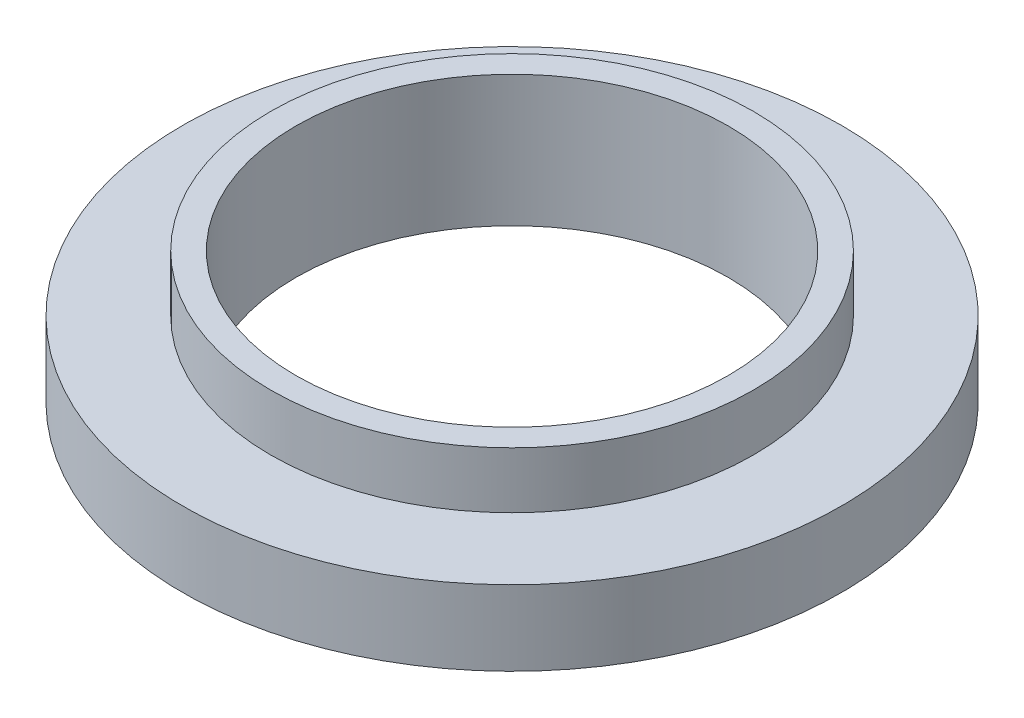
SolidWorks part; units mm, degrees
ref_plane "Front Plane" through (0, 0, 0) normal (0, 0, 1) x (1, 0, 0)
ref_plane "Top Plane" through (0, 0, 0) normal (0, 1, 0) x (1, 0, 0)
ref_plane "Right Plane" through (0, 0, 0) normal (1, 0, 0) x (0, 0, -1)
sketch "Sketch1" plane through (0, 0, 0) normal (0, 0, 1) x (1, 0, 0)
  line L0 (-31.75, 11.0119) -> (-31.75, 30.2842)
  line L1 (-54.35, 0) -> (-35.45, 0) construction
  line L2 (-31.75, 11.0119) -> (-31.75, 30.2842) construction
  line L3 (-31.75, 30.2842) -> (-35.45, 30.2842) construction
  line L4 (-35.45, 0) -> (-35.45, 30.2842) construction
  line L5 (-31.75, 30.2842) -> (-35.45, 30.2842)
  line L6 (-35.45, 30.2842) -> (-35.45, 22.0238)
  line L7 (-35.45, 22.0238) -> (-48.4, 22.0238)
  line L8 (-48.4, 22.0238) -> (-48.4, 11.0119)
  line L9 (-48.4, 11.0119) -> (-35.45, 11.0119) construction
  line L10 (-35.45, 11.0119) -> (-35.45, 0) construction
  line L11 (-35.45, 0) -> (-54.35, 0) construction
  line L12 (-37.9123, 11.0119) -> (-48.4, 11.0119)
  line L13 (0, 0) -> (0, 12.7515) construction
  line L14 (-37.9123, 11.0119) -> (-31.75, 11.0119)
  arc A0 (-35.45, 0) -> (-37.9123, 11.0119) centre (-37.9123, 5.2307) ccw construction
  dimension "D7" = 5.7813
  dimension "D1" = 31.75
  dimension "D2" = 3.7
  dimension "D3" = 30.2842
  dimension "D4" = 8.2604
  dimension "D5" = 48.4
  dimension "D6" = 11.0119
  dimension "D8" = 54.35
revolve "Revolve1" add sketch "Sketch1" angle 360 about L13
sketch "Sketch2" plane through (0, 22.0238, 0) normal (0, 1, 0) x (1, 0, 0)
  line L1 (4.1302, 55.0595) -> (-4.1302, 55.0595)
  line L2 (4.1302, 55.0595) -> (4.1302, 41.7405)
  line L3 (4.1302, 41.7405) -> (-4.1302, 41.7405)
  line L4 (-4.1302, 55.0595) -> (-4.1302, 41.7405)
  line L5 (4.1302, 55.0595) -> (-4.1302, 41.7405) construction
  line L6 (4.1302, 41.7405) -> (-4.1302, 55.0595) construction
  circle A0 centre (0, 0) radius 48.4 construction
  point P0 (0, 48.4)
  dimension "D1" = 8.2604
  dimension "D2" = 55.0595
sketch "Sketch7" plane through (0, 22.0238, 0) normal (0, 1, 0) x (1, 0, 0)
  point P3 (0, 0)
equation "\"D5@Sketch1\"=((\"Spring_inner_dia\"+\"Spring_wire_dia\")/2)*1.1"
equation "\"D6@Sketch1\"=\"Upper_Mount_largest_radius\"/1.68"
equation "\"D4@Sketch1\"=\"Upper_Mount_largest_radius\"/2.23960185"
equation "\"D2@Sketch1\"=\"Upper_Mount_largest_radius\"/5"
equation "\"D7@Sketch1\"=\"Upper_Mount_largest_radius\"/3.2"
equation "\"D1@Sketch1\"=\"Upper_Mount_largest_radius\"+\"Upper_mount_wall_thickness\"+1.25mm"
equation "\"D3@Sketch1\"=\"Upper_Mount_largest_radius\"/0.61087947"
equation "\"D2@Sketch2\"=\"Upper_Mount_largest_radius\"/0.336"
equation "\"D1@Sketch2\"=\"Upper_Mount_largest_radius\"/2.23960185"
equation "\"Upper_Mount_largest_radius\" =18.5"
equation "\"Upper_mount_wall_thickness\" =12"
equation "\"Lower_Mount_piston_rod_length\" =149"
equation "\"Lower_Mount_piston_rod_radius\"\t=4.9101"
equation "\"Piston_orifice_dia\"=0.47773"
equation "\"Spring_inner_dia\" =80"
equation "\"Spring_wire_dia\" =8"
